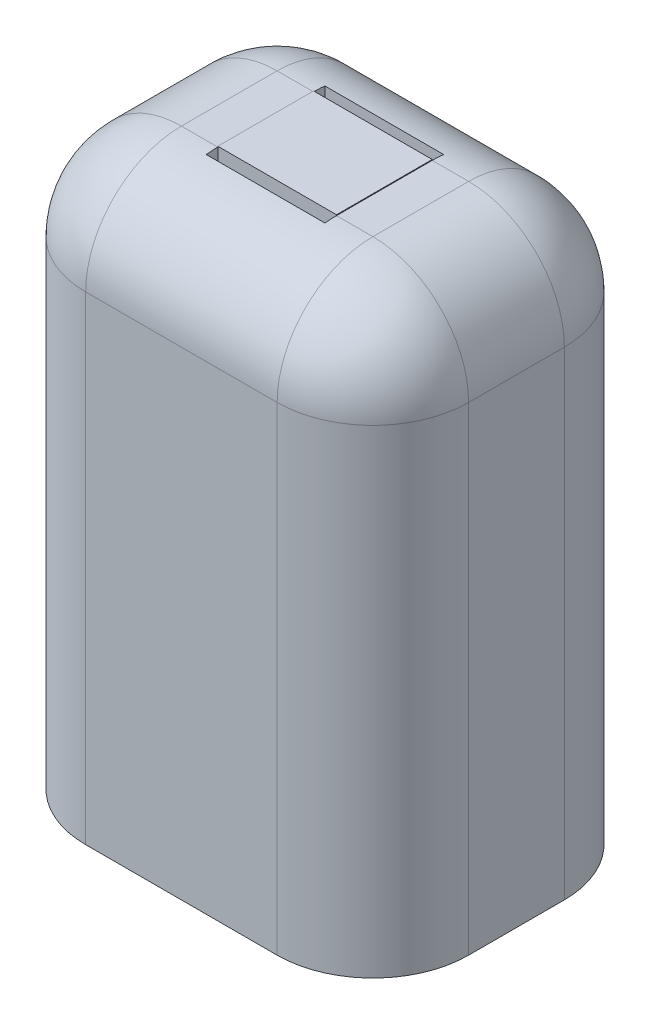
SolidWorks part; units mm, degrees
ref_plane "Front Plane" through (0, 0, 0) normal (0, 0, 1) x (1, 0, 0)
ref_plane "Top Plane" through (0, 0, 0) normal (0, 1, 0) x (1, 0, 0)
ref_plane "Right Plane" through (0, 0, 0) normal (1, 0, 0) x (0, 0, -1)
sketch "Sketch1" plane through (0, 0, 0) normal (0, 0, 1) x (1, 0, 0)
  line L1 (-46.2655, 135.4082) -> (-26.2655, 135.4082)
  line L2 (-46.2655, 135.4082) -> (-46.2655, 105.4082)
  line L3 (-46.2655, 105.4082) -> (-26.2655, 105.4082)
  line L4 (-26.2655, 135.4082) -> (-26.2655, 105.4082)
  line L5 (-46.2655, 135.4082) -> (-26.2655, 105.4082) construction
  line L6 (-46.2655, 105.4082) -> (-26.2655, 135.4082) construction
  point P0 (-36.2655, 120.4082)
  dimension "D1" = 20
  dimension "D2" = 30
extrude "Boss-Extrude1" add sketch "Sketch1" along normal blind 15
sketch "Sketch2" plane through (0, 105.4082, 0) normal (0, -1, 0) x (-1, 0, 0)
  line L0 (36.2655, -15) -> (36.2655, -7.5) construction
  line L1 (39.3655, -4.4) -> (33.1655, -4.4)
  line L2 (39.3655, -4.4) -> (39.3655, -10.6)
  line L3 (39.3655, -10.6) -> (33.1655, -10.6)
  line L4 (33.1655, -4.4) -> (33.1655, -10.6)
  line L5 (39.3655, -4.4) -> (33.1655, -10.6) construction
  line L6 (39.3655, -10.6) -> (33.1655, -4.4) construction
  line L7 (46.2655, -15) -> (26.2655, -15) construction
  line L8 (36.2655, -7.5) -> (26.2655, -7.5) construction
  line L9 (26.2655, -15) -> (26.2655, 0) construction
  point P0 (36.2655, -7.5)
  dimension "D1" = 6.2
  dimension "D2" = 6.2
extrude "Cut-Extrude1" cut sketch "Sketch2" against normal blind 3.25
fillet "Fillet1" radius 5 8 edges at (-26.2655, 135.4082, 7.5) (-36.2655, 135.4082, 15) (-46.2655, 135.4082, 7.5) (-36.2655, 135.4082, 0) (-46.2655, 120.4082, 0) (-46.2655, 120.4082, 15) (-26.2655, 120.4082, 0) (-26.2655, 120.4082, 15)
sketch "Sketch4" plane through (0, 108.6582, 0) normal (0, -1, 0) x (1, 0, 0)
  line L0 (-39.3655, 10.6) -> (-33.1655, 10.6)
  line L1 (-33.1655, 10.6) -> (-33.1655, 4.4)
  line L2 (-33.1655, 4.4) -> (-39.3655, 4.4)
  line L3 (-39.3655, 4.4) -> (-39.3655, 10.6)
extrude "Cut-Extrude2" cut sketch "Sketch4" against normal blind 68
sketch "Sketch6" plane through (-39.3655, 0, 0) normal (1, 0, 0) x (0, 0, -1)
  line L0 (-10, 135.4082) -> (-10, 130.4082) construction
  line L1 (-10, 135.4497) -> (-5, 135.4497)
  line L2 (-10, 135.4497) -> (-10, 134.4497)
  line L3 (-10, 134.4497) -> (-5, 134.4497)
  line L4 (-5, 135.4497) -> (-5, 134.4497)
  line L5 (-5, 130.4082) -> (-5, 135.4082) construction
  dimension "D1" = 1
  dimension "D2" = 5
extrude "Boss-Extrude3" add sketch "Sketch6" along normal blind 6.2
